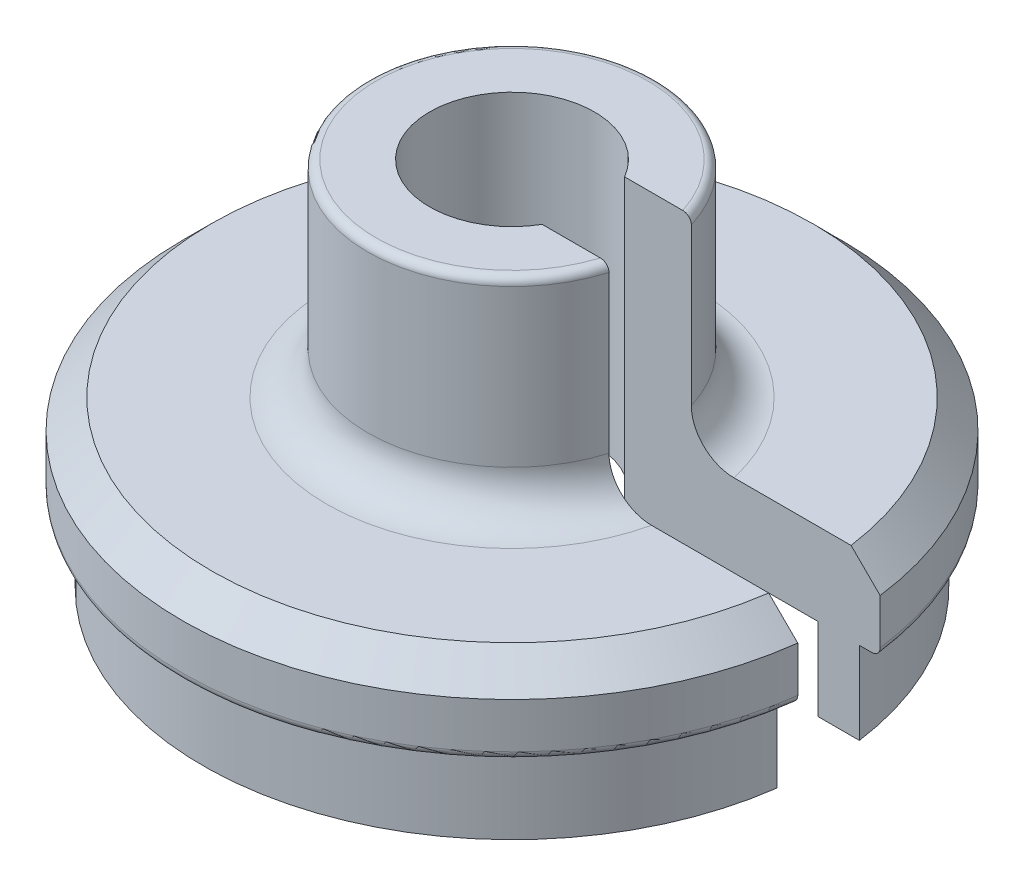
SolidWorks part; units mm, degrees
ref_plane "前视基准面" through (0, 0, 0) normal (0, 0, 1) x (1, 0, 0)
ref_plane "上视基准面" through (0, 0, 0) normal (0, 1, 0) x (1, 0, 0)
ref_plane "右视基准面" through (0, 0, 0) normal (1, 0, 0) x (0, 0, -1)
sketch "草图1" plane through (0, 0, 0) normal (0, 0, 1) x (1, 0, 0)
  line L0 (-1.5962, 5) -> (-0.0962, 5)
  line L1 (-0.0962, 5) -> (-0.0962, 0)
  line L2 (-0.0962, 0) -> (4.4038, 0)
  line L3 (4.4038, 0) -> (4.4038, -2)
  line L4 (4.4038, -2) -> (-1.5962, -2)
  line L5 (-1.5962, -2) -> (-1.5962, 5)
  line L6 (-3.5962, 17.535) -> (-3.5962, -18.5683) construction
  dimension "D1" = 1.5
  dimension "D2" = 5
  dimension "D3" = 6
  dimension "D4" = 2
  dimension "D5" = 8
revolve "旋转1" add sketch "草图1" angle 360 mid plane about L6
sketch "草图2" plane through (0, 0, 0) normal (0, 0, 1) x (1, 0, 0)
  line L1 (-3.5962, 5.6879) -> (5.8229, 5.6879)
  line L2 (-3.5962, 5.6879) -> (-3.5962, -6.1048)
  line L3 (-3.5962, -6.1048) -> (5.8229, -6.1048)
  line L4 (5.8229, 5.6879) -> (5.8229, -6.1048)
extrude "切除-拉伸1" cut sketch "草图2" against normal mid plane 2
fillet "圆角1" radius 0.2 1 edges at (-7.0962, 5, 0)
chamfer "倒角1" distance 0.7 angle 45 1 edges at (-11.5962, 0, 0)
fillet "圆角2" radius 0.2 1 edges at (-11.5962, -2, 0)
fillet "圆角3" radius 1 1 edges at (-7.0962, 0, 0)
sketch "草图3" plane through (0, -2, 0) normal (0, -1, 0) x (1, 0, 0)
  line L0 (-1.8641, 1) -> (5.8577, 1) construction
  line L1 (-1.8641, -1) -> (6.1066, -1) construction
  line L2 (2.8265, -1) -> (3.8369, -1)
  line L3 (2.8265, 1) -> (3.8369, 1)
  arc A0 (2.8265, 1) -> (2.8265, -1) centre (-3.5962, 0) ccw
  arc A1 (3.8369, 1) -> (3.8369, -1) centre (-3.5962, 0) ccw
  dimension "D1" = 15
  dimension "D2" = 13
extrude "凸台-拉伸1" add sketch "草图3" along normal blind 2
